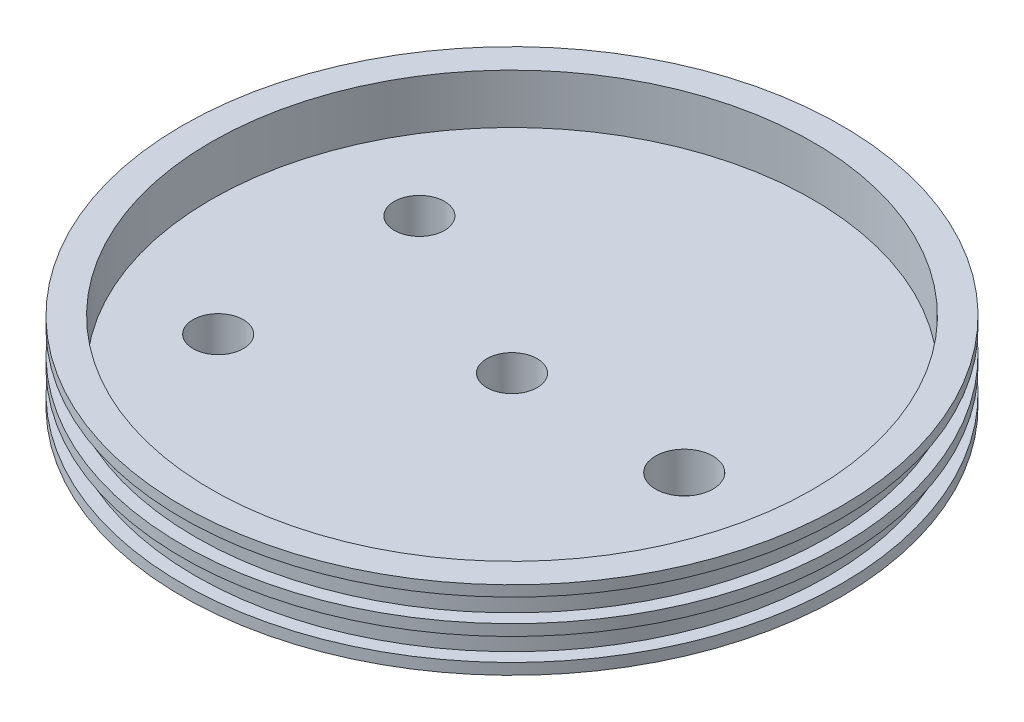
SolidWorks part; units mm, degrees
material "6061-T6 (SS)"
ref_plane "Front Plane" through (0, 0, 0) normal (0, 0, 1) x (1, 0, 0)
ref_plane "Top Plane" through (0, 0, 0) normal (0, 1, 0) x (1, 0, 0)
ref_plane "Right Plane" through (0, 0, 0) normal (1, 0, 0) x (0, 0, -1)
sketch "Sketch1" plane through (0, 0, 0) normal (0, 0, 1) x (1, 0, 0)
  line L0 (0, 48.1922) -> (0, -25.6743) construction
  line L1 (0, 0) -> (72.898, 0)
  line L2 (72.898, 0) -> (72.898, 2.4638)
  line L3 (72.898, 2.4638) -> (69.977, 2.4638)
  line L4 (69.977, 2.4638) -> (69.977, 7.4422)
  line L5 (69.977, 7.4422) -> (72.898, 7.4422)
  line L6 (72.898, 7.4422) -> (72.898, 9.906)
  line L7 (72.898, 9.906) -> (69.977, 9.906)
  line L8 (66.548, 17.3482) -> (66.548, 6.35)
  line L9 (66.548, 6.35) -> (0, 6.35)
  line L10 (0, 6.35) -> (0, 0)
  line L11 (69.977, 9.906) -> (69.977, 14.986)
  line L12 (69.977, 14.986) -> (72.898, 14.986)
  line L13 (72.898, 14.986) -> (72.898, 17.3482)
  line L14 (72.898, 17.3482) -> (66.548, 17.3482)
  dimension "D1" = 145.796
  dimension "D2" = 4.9784
  dimension "D3" = 2.921
  dimension "D4" = 9.906
  dimension "D5" = 6.35
  dimension "D6" = 6.35
  dimension "D7" = 5.08
  dimension "D8" = 9.906
revolve "Revolve1" add sketch "Sketch1" angle 360 about L0
sketch "Sketch6" plane through (0, 0, 0) normal (0, -1, 0) x (1, 0, 0)
  circle A0 centre (0, 0) radius 66.04
  dimension "D1" = 132.08
extrude "Boss-Extrude1" add sketch "Sketch6" along normal blind 2.54
hole_wizard "Pipe Tap Drill for 1/4 Tap - GN2" positions "Sketch2" profile "Sketch3" hole size "1/4" standard "ANSI Inch" end condition through all
sketch "Sketch2" plane through (0, 6.35, 0) normal (0, 1, 0) x (1, 0, 0)
  point P4 (0, 0)
  dimension "D1" = 0
sketch "Sketch3" plane through (0, 6.35, 0) normal (1, 0, 0) x (0, 0, 1)
  line L0 (0, 0) -> (0, 8.89)
  line L1 (0, 8.89) -> (5.5626, 8.89)
  line L2 (5.5626, 8.89) -> (5.5626, 0)
  line L5 (5.5626, 0) -> (0, 0)
  line L11 (0, -6.35) -> (0, 107.95) construction
  dimension "Thru Hole Dia." = 11.1252
  dimension "Thru Hole Depth" = 8.89
fillet "CNC ID Fillet" [suppressed] radius 0.1778
fillet "CNC OD Fillet" [suppressed] radius 0.127
chamfer "CNC Chamfers" [suppressed] distance 0.254 angle 45
fillet "CNC Bore Fillet" [suppressed] radius 0.254
sketch "Sketch7" plane through (0, -2.54, 0) normal (0, -1, 0) x (-1, 0, 0)
  circle A0 centre (-38.1, 0) radius 6.35
  dimension "D1" = 12.7
  dimension "D2" = 38.1
extrude "Cut-Extrude1-Siphon" cut sketch "Sketch7" against normal through all
hole_wizard "Pipe Tap Drill for 1/4 Tap - Relief Valve" positions "Sketch13" profile "Sketch14" hole size "1/4" standard "ANSI Inch" end condition through all
sketch "Sketch13" plane through (0, -2.54, 0) normal (0, -1, 0) x (-1, 0, 0)
  point P4 (40.358, 19.8786)
sketch "Sketch14" plane through (-40.358, -2.54, -19.8786) normal (1, 0, 0) x (0, 0, -1)
  line L0 (0, 0) -> (0, 19.8882)
  line L1 (0, 19.8882) -> (5.5626, 19.8882)
  line L2 (5.5626, 19.8882) -> (5.5626, 0)
  line L5 (5.5626, 0) -> (0, 0)
  line L11 (0, -6.35) -> (0, 107.95) construction
  dimension "Thru Hole Dia." = 11.1252
  dimension "Thru Hole Depth" = 19.8882
hole_wizard "Pipe Tap Drill for 1/4 Tap - Vent Valve" positions "Sketch15" profile "Sketch16" hole size "1/4" standard "ANSI Inch" end condition through all
sketch "Sketch15" plane through (0, -2.54, 0) normal (0, -1, 0) x (-1, 0, 0)
  point P4 (39.9614, -25.0312)
sketch "Sketch16" plane through (-39.9614, -2.54, 25.0312) normal (1, 0, 0) x (0, 0, -1)
  line L0 (0, 0) -> (0, 19.8882)
  line L1 (0, 19.8882) -> (5.5626, 19.8882)
  line L2 (5.5626, 19.8882) -> (5.5626, 0)
  line L5 (5.5626, 0) -> (0, 0)
  line L11 (0, -6.35) -> (0, 107.95) construction
  dimension "Thru Hole Dia." = 11.1252
  dimension "Thru Hole Depth" = 19.8882
